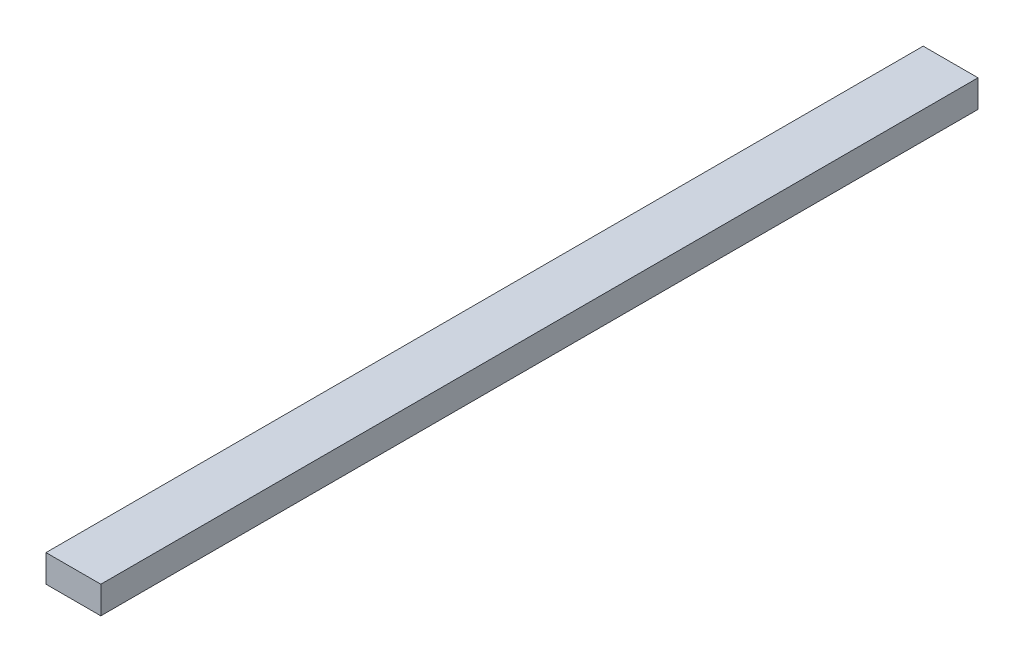
SolidWorks part; units mm, degrees
ref_plane "Front Plane" through (0, 0, 0) normal (0, 0, 1) x (1, 0, 0)
ref_plane "Top Plane" through (0, 0, 0) normal (0, 1, 0) x (1, 0, 0)
ref_plane "Right Plane" through (0, 0, 0) normal (1, 0, 0) x (0, 0, -1)
sketch "Sketch1" plane through (0, 0, 0) normal (0, 0, 1) x (1, 0, 0)
  line L1 (-15, 7.5) -> (15, 7.5)
  line L2 (-15, 7.5) -> (-15, -7.5)
  line L3 (-15, -7.5) -> (15, -7.5)
  line L4 (15, 7.5) -> (15, -7.5)
  line L5 (-15, 7.5) -> (15, -7.5) construction
  line L6 (-15, -7.5) -> (15, 7.5) construction
  point P0 (0, 0)
  dimension "D1" = 30
  dimension "D2" = 15
extrude "Boss-Extrude1" add sketch "Sketch1" along normal blind 480
